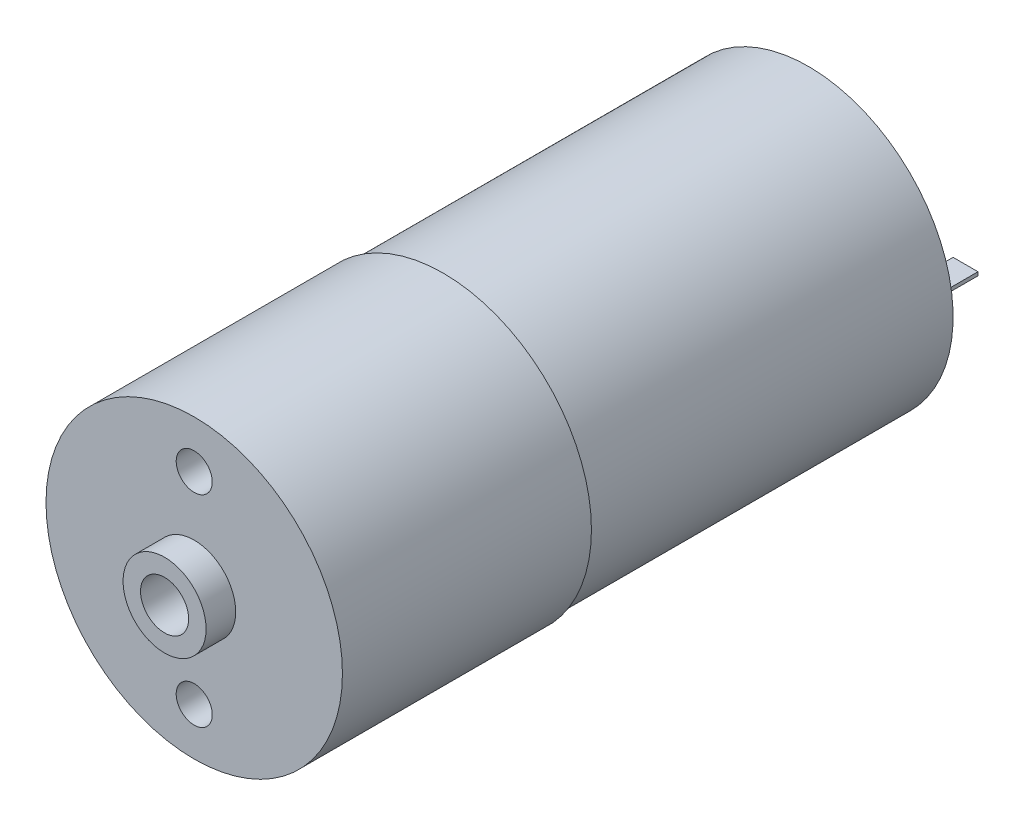
SolidWorks part; units mm, degrees
ref_plane "Front Plane" through (0, 0, 0) normal (0, 0, 1) x (1, 0, 0)
ref_plane "Top Plane" through (0, 0, 0) normal (0, 1, 0) x (1, 0, 0)
ref_plane "Right Plane" through (0, 0, 0) normal (1, 0, 0) x (0, 0, -1)
sketch "S01 - 25 mm 47-to-1 gearbox" plane through (0, 0, 0) normal (0, 0, 1) x (1, 0, 0)
  circle A0 centre (0, 0) radius 12.5
  dimension "D1" = 25
extrude "01 - 25 mm 47-to-1 gearbox" add sketch "S01 - 25 mm 47-to-1 gearbox" along normal blind 21 from offset 21
sketch "S02 - 24.4 mm motor can" plane through (0, 0, 0) normal (0, 0, 1) x (1, 0, 0)
  circle A0 centre (0, 0) radius 12.2
  dimension "D1" = 24.4
extrude "02 - 24.4 mm motor can" add sketch "S02 - 24.4 mm motor can" along normal blind 30.8 from offset 51.8
sketch "S03 - Rear shaft boss" plane through (0, 0, 0) normal (0, 0, 1) x (1, 0, 0)
  circle A0 centre (0, 0) radius 3.2
  dimension "D1" = 6.4
extrude "03 - Rear shaft boss" add sketch "S03 - Rear shaft boss" along normal blind 1.5 from offset 53.3
sketch "S04 - Rear motor terminal -1" plane through (0, 0, 0) normal (0, 0, 1) x (1, 0, 0)
  line L0 (-10.1, -0.15) -> (-8, -0.15)
  line L1 (-8, -0.15) -> (-8, 0.15)
  line L2 (-8, 0.15) -> (-10.1, 0.15)
  line L3 (-10.1, 0.15) -> (-10.1, -0.15)
  dimension "D1" = 8
  dimension "D2" = 10.1
  dimension "D3" = 0.15
  dimension "D4" = 0.15
extrude "04 - Rear motor terminal -1" add sketch "S04 - Rear motor terminal -1" along normal blind 4.2 from offset 56
sketch "S05 - Rear motor terminal 1" plane through (0, 0, 0) normal (0, 0, 1) x (1, 0, 0)
  line L0 (8, -0.15) -> (10.1, -0.15)
  line L1 (10.1, -0.15) -> (10.1, 0.15)
  line L2 (10.1, 0.15) -> (8, 0.15)
  line L3 (8, 0.15) -> (8, -0.15)
  dimension "D1" = 8
  dimension "D2" = 10.1
  dimension "D3" = 0.15
  dimension "D4" = 0.15
extrude "05 - Rear motor terminal 1" add sketch "S05 - Rear motor terminal 1" along normal blind 4.2 from offset 56
sketch "S06 - Face mounting M3 thread envelopes" plane through (0, 0, 0) normal (0, 0, 1) x (1, 0, 0)
  circle A0 centre (0, 8.5) radius 1.52
  circle A1 centre (0, -8.5) radius 1.52
  dimension "D1" = 3.04
  dimension "D2" = 3.04
  dimension "D3" = 8.5
  dimension "D4" = 8.5
extrude "06 - Face mounting M3 thread envelopes" cut sketch "S06 - Face mounting M3 thread envelopes" along normal blind 6.1 from offset 6 offset against normal yes
sketch "S07 - Motor shaft pilot" plane through (0, 0, 0) normal (0, 0, 1) x (1, 0, 0)
  circle A0 centre (0, 0) radius 3.5
  dimension "D1" = 7
extrude "07 - Motor shaft pilot" add sketch "S07 - Motor shaft pilot" along normal blind 2.5
sketch "S08 - Output shaft clearance" plane through (0, 0, 0) normal (0, 0, 1) x (1, 0, 0)
  circle A0 centre (0, 0) radius 2.03
  dimension "D1" = 4.06
extrude "08 - Output shaft clearance" cut sketch "S08 - Output shaft clearance" along normal blind 3.6 from offset 1
